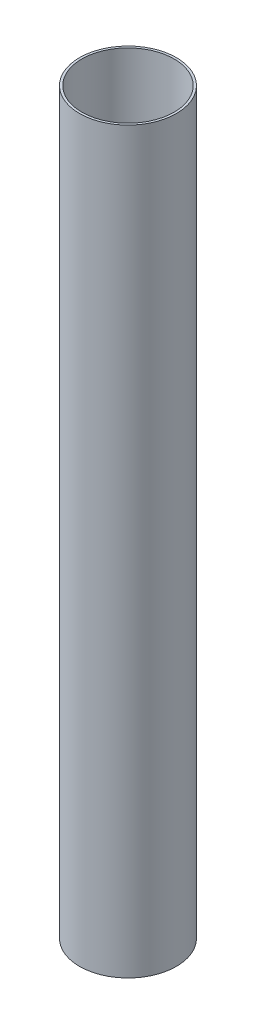
SolidWorks part; units mm, degrees
material "Thornel Mat VMA"
ref_plane "Front Plane" through (0, 0, 0) normal (0, 0, 1) x (1, 0, 0)
ref_plane "Top Plane" through (0, 0, 0) normal (0, 1, 0) x (1, 0, 0)
ref_plane "Right Plane" through (0, 0, 0) normal (1, 0, 0) x (0, 0, -1)
sketch "Sketch1" plane through (0, 0, 0) normal (0, 1, 0) x (1, 0, 0)
  circle A0 centre (0, 0) radius 33.3248
  circle A1 centre (0, 0) radius 31.75
  dimension "D1" = 63.5
  dimension "D2" = 1.5748
extrude "Boss-Extrude1" add sketch "Sketch1" along normal blind 508
